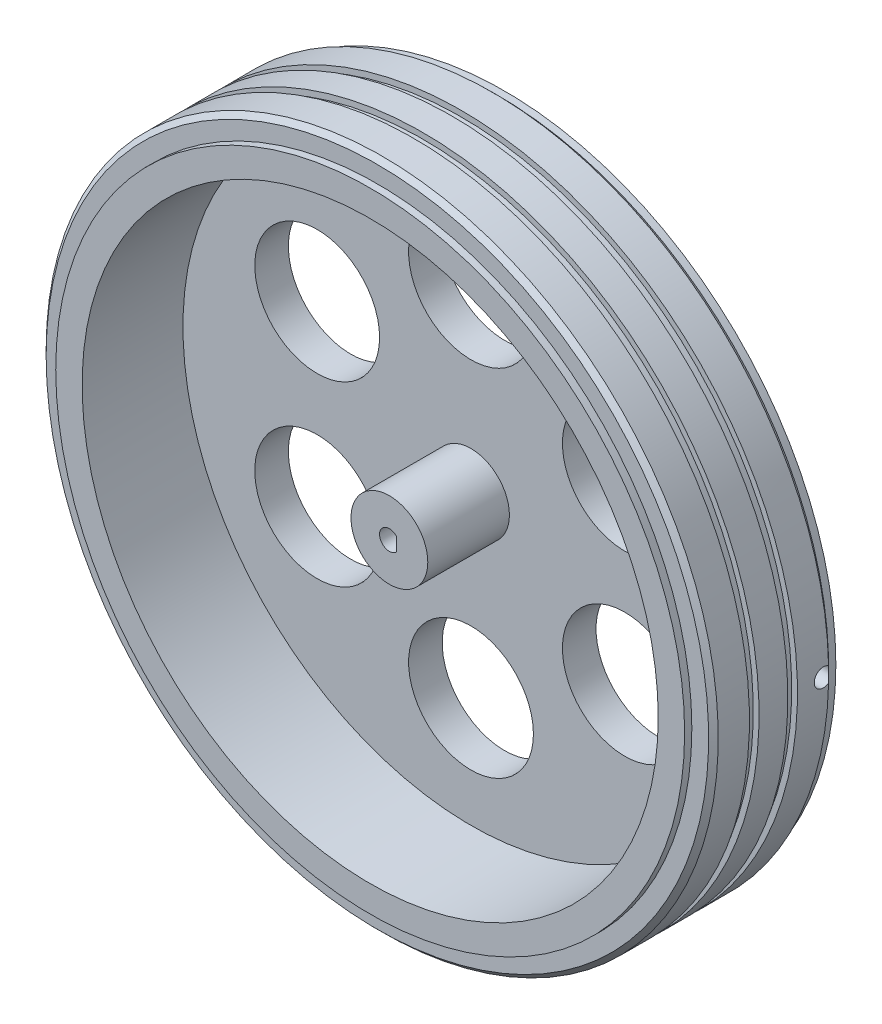
SolidWorks part; units mm, degrees
ref_plane "Front Plane" through (0, 0, 0) normal (0, 0, 1) x (1, 0, 0)
ref_plane "Top Plane" through (0, 0, 0) normal (0, 1, 0) x (1, 0, 0)
ref_plane "Right Plane" through (0, 0, 0) normal (1, 0, 0) x (0, 0, -1)
sketch "Sketch1" plane through (0, 0, 0) normal (0, 0, 1) x (1, 0, 0)
  circle A0 centre (0, 0) radius 64
  circle A1 centre (0, 0) radius 60
extrude "Rim" add sketch "Sketch1" along normal blind 28
sketch "Sketch2" plane through (0, 0, 0) normal (0, 0, 1) x (1, 0, 0)
  circle A0 centre (0, 0) radius 65.5
  circle A1 centre (0, 0) radius 63
extrude "Inner_bead_lip" add sketch "Sketch2" along normal blind 1.5
ref_plane "P_Front_26p5" through (0, 0, 26.5) normal (0, 0, 1) x (1, 0, 0)
sketch "Sketch3" plane through (0, 0, 26.5) normal (0, 0, 1) x (1, 0, 0)
  circle A0 centre (0, 0) radius 65.5
  circle A1 centre (0, 0) radius 63
extrude "Outer_bead_lip" add sketch "Sketch3" along normal blind 1.5
sketch "Sketch4" plane through (0, 0, 0) normal (0, 0, 1) x (1, 0, 0)
  circle A0 centre (0, 0) radius 61
extrude "Web" add sketch "Sketch4" along normal blind 7
sketch "Sketch5" plane through (0, 0, 0) normal (0, 0, 1) x (1, 0, 0)
  circle A0 centre (0, 0) radius 8
extrude "Hub_boss" add sketch "Sketch5" along normal blind 24
ref_plane "P_Front_m1" through (0, 0, -1) normal (0, 0, 1) x (1, 0, 0)
sketch "Sketch6" plane through (0, 0, -1) normal (0, 0, 1) x (1, 0, 0)
  circle A0 centre (32.0429, 18.5) radius 13
  circle A1 centre (0, 37) radius 13
  circle A2 centre (-32.0429, 18.5) radius 13
  circle A3 centre (-32.0429, -18.5) radius 13
  circle A4 centre (0, -37) radius 13
  circle A5 centre (32.0429, -18.5) radius 13
extrude "Lightening_holes" cut sketch "Sketch6" along normal blind 9
sketch "Sketch7" plane through (0, 0, -1) normal (0, 0, 1) x (1, 0, 0)
  line L0 (1.5, -1.3973) -> (1.5, 1.3973)
  arc A0 (1.5, 1.3973) -> (1.5, -1.3973) centre (0, 0) ccw
extrude "D_bore_4mm" cut sketch "Sketch7" along normal blind 30
sketch "Sketch8" plane through (0, 0, 0) normal (1, 0, 0) x (0, 0, -1)
  line L0 (-1.5, 64) -> (-26.5, 64)
  line L1 (-26.5, 64) -> (-26.5, 69)
  line L2 (-26.5, 69) -> (-25.5, 70)
  line L3 (-25.5, 70) -> (-19, 70)
  line L4 (-19, 70) -> (-19, 68.8)
  line L5 (-19, 68.8) -> (-17, 68.8)
  line L6 (-17, 68.8) -> (-17, 70)
  line L7 (-17, 70) -> (-11, 70)
  line L8 (-11, 70) -> (-11, 68.8)
  line L9 (-11, 68.8) -> (-9, 68.8)
  line L10 (-9, 68.8) -> (-9, 70)
  line L11 (-9, 70) -> (-2.5, 70)
  line L12 (-2.5, 70) -> (-1.5, 69)
  line L13 (-1.5, 69) -> (-1.5, 64)
  line L14 (0, 0) -> (-30, 0) construction
revolve "Tyre" add sketch "Sketch8" angle 360 about L14
sketch "Sketch9" plane through (0, 0, 0) normal (0, 0, 1) x (1, 0, 0)
  circle A0 centre (0, 0) radius 69
  circle A1 centre (0, 0) radius 64
extrude "Bed_ring" add sketch "Sketch9" along normal blind 1.5
sketch "Sketch10" plane through (0, 0, 0) normal (1, 0, 0) x (0, 0, -1)
  circle A0 centre (-3.6, 0) radius 1.3
extrude "Grub_screw_M3" cut sketch "Sketch10" along normal blind 9
ref_plane "P_Right_8p5" through (8.5, 0, 0) normal (1, 0, 0) x (0, 0, -1)
sketch "Sketch11" plane through (8.5, 0, 0) normal (1, 0, 0) x (0, 0, -1)
  circle A0 centre (-3.6, 0) radius 1.9
extrude "Grub_key_access" cut sketch "Sketch11" along normal blind 62.5
